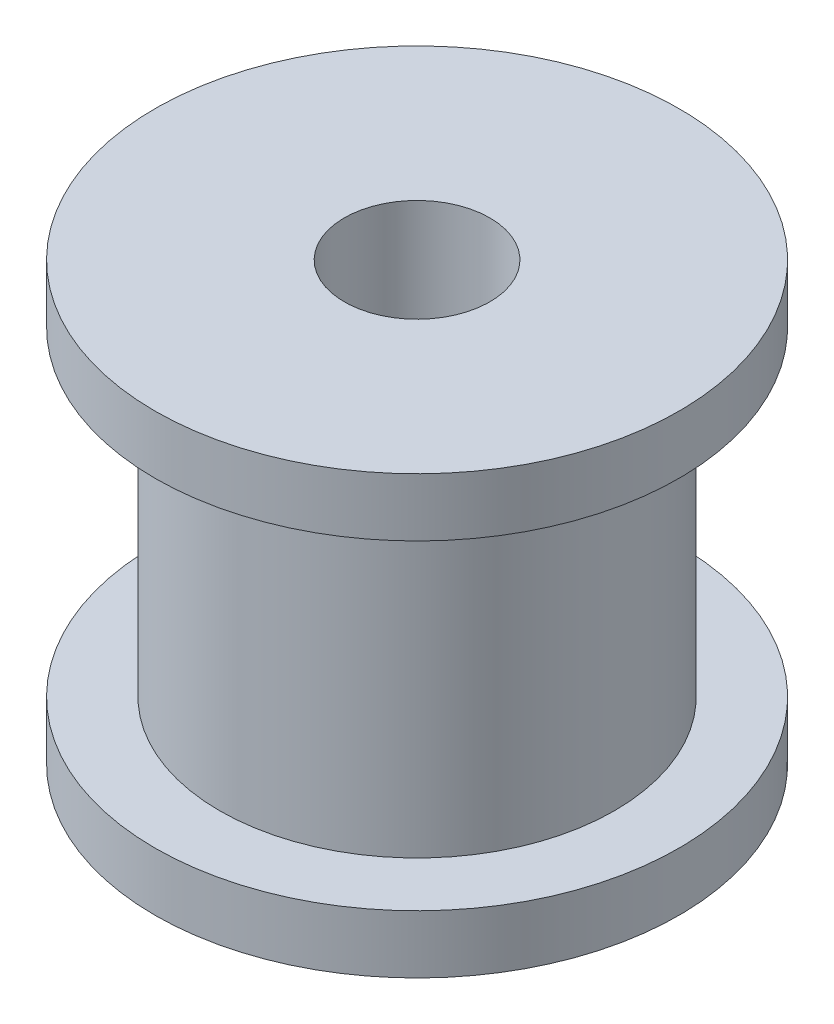
SolidWorks part; units mm, degrees
ref_plane "前视基准面" through (0, 0, 0) normal (0, 0, 1) x (1, 0, 0)
ref_plane "上视基准面" through (0, 0, 0) normal (0, 1, 0) x (1, 0, 0)
ref_plane "右视基准面" through (0, 0, 0) normal (1, 0, 0) x (0, 0, -1)
sketch "草图1" plane through (0, 0, 0) normal (0, 1, 0) x (1, 0, 0)
  circle A0 centre (0, 0) radius 9
  dimension "D1" = 18
extrude "凸台-拉伸1" add sketch "草图1" along normal blind 2
sketch "草图2" plane through (0, 2, 0) normal (0, 1, 0) x (1, 0, 0)
  circle A0 centre (0, 0) radius 6.78
  dimension "D1" = 13.56
extrude "凸台-拉伸2" add sketch "草图2" along normal blind 11
sketch "草图3" plane through (0, 13, 0) normal (0, 1, 0) x (1, 0, 0)
  circle A0 centre (0, 0) radius 9
  circle A1 centre (0, 0) radius 9 construction
extrude "凸台-拉伸3" add sketch "草图3" along normal blind 2
sketch "草图5" plane through (0, 0, 0) normal (0, -1, 0) x (1, 0, 0)
  circle A0 centre (0, 0) radius 2.5
  dimension "D1" = 5
extrude "切除-拉伸1" cut sketch "草图5" against normal through all
